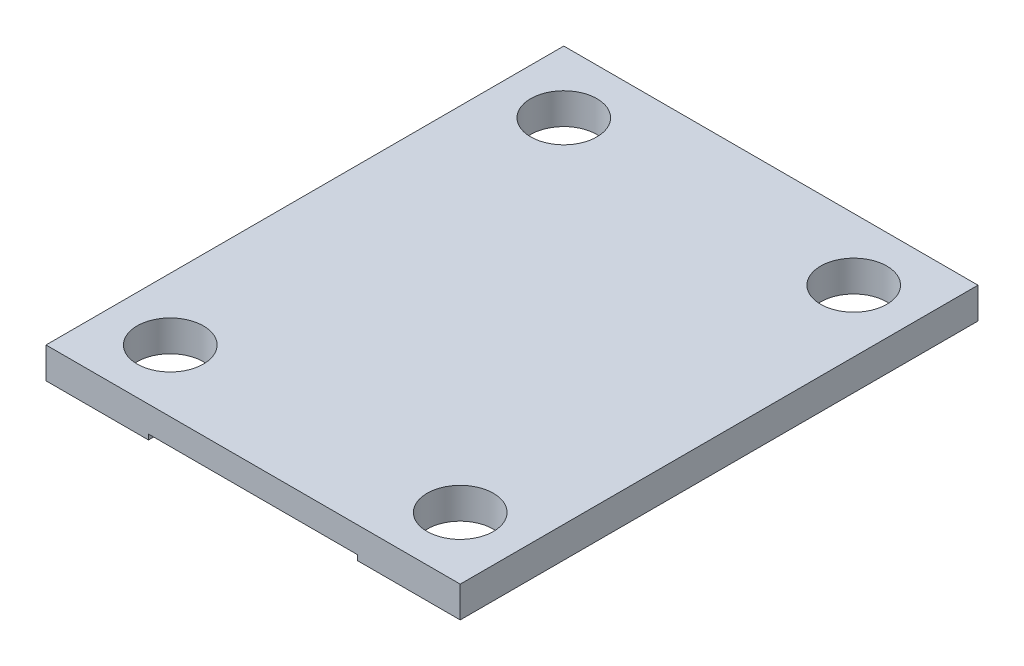
SolidWorks part; units mm, degrees
ref_plane "前视基准面" through (0, 0, 0) normal (0, 0, 1) x (1, 0, 0)
ref_plane "上视基准面" through (0, 0, 0) normal (0, 1, 0) x (1, 0, 0)
ref_plane "右视基准面" through (0, 0, 0) normal (1, 0, 0) x (0, 0, -1)
ref_plane "基准面4" through (0, 0, 0) normal (0, -1, 0) x (1, 0, 0)
sketch "草图1" plane through (0, 0, 0) normal (0, -1, 0) x (1, 0, 0)
  line L0 (10, -15) -> (10, 10)
  line L1 (10, 10) -> (-10, 10)
  line L2 (-10, 10) -> (-10, -15)
  line L3 (-10, -15) -> (10, -15)
extrude "凸台-拉伸1" add sketch "草图1" against normal blind 1.5
sketch "草图2" plane through (0, 0, 0) normal (0, -1, 0) x (1, 0, 0)
  line L0 (-5.05, 10) -> (-5.05, -7.5)
  line L1 (-5.05, -7.5) -> (5.05, -7.5)
  line L2 (5.05, -7.5) -> (5.05, 10)
  line L3 (5.05, 10) -> (-5.05, 10)
extrude "切除-拉伸1" cut sketch "草图2" against normal blind 0.25
hole_wizard "Ø3.2 (3.2) 直径孔1" positions "草图4" profile "草图3" hole size "Ø3.2" standard "ANSI Metric"
sketch "草图4" plane through (0, 0, 0) normal (0, -1, 0) x (-1, 0, 0)
  point P0 (-7, -7)
  point P1 (-7, 12)
sketch "草图3" plane through (7, 0, 7) normal (1, 0, 0) x (0, 0, -1)
  line L0 (0, 0) -> (0, 1.5)
  line L1 (0, 1.5) -> (1.6, 1.5)
  line L2 (1.6, 1.5) -> (1.6, 0)
  line L5 (1.6, 0) -> (0, 0)
  line L11 (0, -6.35) -> (0, 107.95) construction
  dimension "通孔孔直径" = 3.2
  dimension "通孔孔深度" = 1.5
hole_wizard "Ø3.2 (3.2) 直径孔2" positions "草图6" profile "草图5" hole size "Ø3.2" standard "ANSI Metric"
sketch "草图6" plane through (0, 1.5, 0) normal (0, 1, 0) x (1, 0, 0)
  point P0 (-7, -7)
  point P1 (-7, 12)
sketch "草图5" plane through (-7, 1.5, 7) normal (1, 0, 0) x (0, 0, 1)
  line L0 (0, 0) -> (0, 1.5)
  line L1 (0, 1.5) -> (1.6, 1.5)
  line L2 (1.6, 1.5) -> (1.6, 0)
  line L5 (1.6, 0) -> (0, 0)
  line L11 (0, -6.35) -> (0, 107.95) construction
  dimension "通孔孔直径" = 3.2
  dimension "通孔孔深度" = 1.5
